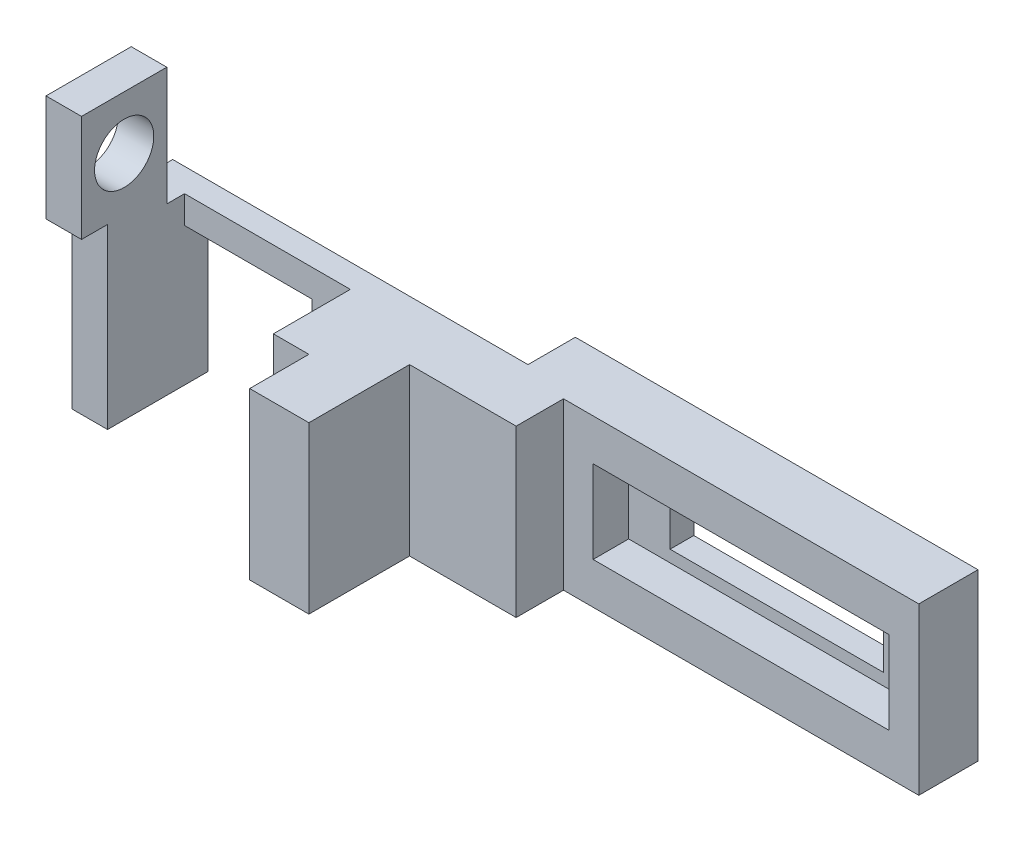
SolidWorks part; units mm, degrees
ref_plane "Front Plane" through (0, 0, 0) normal (0, 0, 1) x (1, 0, 0)
ref_plane "Top Plane" through (0, 0, 0) normal (0, 1, 0) x (1, 0, 0)
ref_plane "Right Plane" through (0, 0, 0) normal (1, 0, 0) x (0, 0, -1)
sketch "Sketch1" plane through (0, 0, 0) normal (0, 1, 0) x (1, 0, 0)
  line L1 (25, 0) -> (25, 8.5)
  line L2 (25, 8.5) -> (34, 8.5)
  line L8 (0, 13.5) -> (30, 13.5)
  line L9 (30, 13.5) -> (30, 17.5)
  line L10 (30, 17.5) -> (64, 17.5)
  line L11 (64, 17.5) -> (64, 12.5)
  line L12 (20, 0) -> (20, 5)
  line L13 (20, 5) -> (0, 5)
  line L14 (20, 0) -> (25, 0)
  line L15 (0, 5) -> (0, 13.5)
  line L17 (0, 0) -> (37.5449, 0) construction
  line L18 (34, 8.5) -> (34, 12.5)
  line L19 (34, 12.5) -> (64, 12.5)
  point P3 (34, 13.5)
  point P15 (0, 0)
  point P17 (62.4601, 13.1956)
  dimension "D1" = 5
  dimension "D2" = 9
  dimension "D3" = 5
  dimension "D4" = 30
  dimension "D5" = 4
  dimension "D6" = 8.5
  dimension "D7" = 5
  dimension "D8" = 20
  dimension "D9" = 5
  dimension "D10" = 4
extrude "Boss-Extrude1" add sketch "Sketch1" along normal blind 14
sketch "Sketch2" plane through (0, 0, -12.5) normal (0, 0, 1) x (1, 0, 0)
  line L0 (64, 7) -> (34, 7) construction
  line L1 (61.5, 3.5) -> (36.5, 3.5)
  line L2 (61.5, 3.5) -> (61.5, 10.5)
  line L3 (61.5, 10.5) -> (36.5, 10.5)
  line L4 (36.5, 3.5) -> (36.5, 10.5)
  line L6 (64, 14) -> (64, 0) construction
  line L7 (49, 3.5) -> (49, 10.5) construction
  line L8 (34, 14) -> (34, 0) construction
  line L11 (61.5, 7) -> (36.5, 7) construction
  line L14 (49, 14) -> (49, 0) construction
  line L15 (34, 14) -> (64, 14) construction
  line L16 (34, 0) -> (64, 0) construction
  dimension "D1" = 25
  dimension "D2" = 7
extrude "Cut-Extrude3" cut sketch "Sketch2" against normal blind 3
sketch "Sketch10" plane through (0, 0, -15.5) normal (0, 0, 1) x (1, 0, 0)
  line L0 (49, 10.5) -> (49, 3.5) construction
  line L1 (58, 9.5) -> (40, 9.5)
  line L2 (58, 9.5) -> (58, 4.5)
  line L3 (58, 4.5) -> (40, 4.5)
  line L4 (40, 9.5) -> (40, 4.5)
  line L5 (58, 9.5) -> (40, 4.5) construction
  line L6 (58, 4.5) -> (40, 9.5) construction
  line L7 (61.5, 10.5) -> (36.5, 10.5) construction
  line L8 (36.5, 3.5) -> (61.5, 3.5) construction
  line L9 (36.5, 7) -> (61.5, 7) construction
  line L10 (36.5, 10.5) -> (36.5, 3.5) construction
  line L11 (61.5, 3.5) -> (61.5, 10.5) construction
  point P0 (49, 7)
  point P11 (49, 9.5)
  point P18 (40, 7)
  dimension "D1" = 18
  dimension "D2" = 5
extrude "Cut-Extrude4" cut sketch "Sketch10" against normal through all
sketch "Sketch11" plane through (0, 0, 0) normal (-1, 0, 0) x (0, 0, 1)
  line L7 (-13.5, 14) -> (-5, 14) construction
  line L12 (-10, 14) -> (-10, 24)
  line L18 (-5, 14) -> (-5, 15)
  line L20 (-10, 14) -> (-5, 14)
  line L23 (-10, 24) -> (-2.8009, 24)
  line L24 (-2.8009, 24) -> (-2.8009, 15)
  line L25 (-2.8009, 15) -> (-5, 15)
  point P0 (-2.8009, 19.7356)
  dimension "D1" = 9
  dimension "D2" = 5
  dimension "D3" = 10
extrude "Boss-Extrude8" add sketch "Sketch11" against normal blind 3
sketch "Sketch12" plane through (3, 0, 0) normal (1, 0, 0) x (0, 0, -1)
  line L0 (2.8009, 15) -> (2.8009, 24) construction
  line L1 (5, 15) -> (2.8009, 15) construction
  circle A0 centre (5.3009, 17.5) radius 2.5
  point P2 (7.543, 27.6234)
  dimension "D1" = 5
extrude "Boss-Extrude9" [suppressed] add sketch "Sketch12" along normal blind 9
ref_plane "Plane1" through (10, 0, 0) normal (-1, 0, 0) x (0, 0, 1)
sketch "Sketch14" plane through (0, 0, -13.5) normal (0, 0, -1) x (-1, 0, 0)
  line L0 (-30, 0) -> (0, 0) construction
  line L1 (-10, 0) -> (-3, 0)
  line L2 (-10, 0) -> (-10, 12)
  line L3 (-10, 12) -> (-3, 12)
  line L4 (-3, 0) -> (-3, 12)
  line L5 (-3, 24) -> (-3, 14) construction
  dimension "D1" = 12
  dimension "D2" = 7
extrude "Cut-Extrude6" [suppressed] cut sketch "Sketch14" against normal blind 9
sketch "Sketch13" plane through (10, 0, 0) normal (-1, 0, 0) x (0, 0, 1)
  line L1 (-13.5, 14) -> (-10, 14) construction
  line L2 (-13.5, 14) -> (-5, 14)
  line L3 (-5, 14) -> (-5, 0)
  line L7 (-5, 0) -> (-7.0993, 0)
  line L8 (-7.0993, 0) -> (-13.5, 14)
  line L9 (-13.5, 0) -> (-5, 0) construction
  line L10 (-5, 14) -> (-5, 0) construction
  line L11 (-5, 15) -> (-5, 0) construction
  line L13 (-13.5, 14) -> (-13.5, 0) construction
  line L14 (-17.5, 14) -> (-13.5, 14) construction
  point P1 (-8.672, 0)
  point P5 (0, 0)
  point P9 (-11.089, 14)
  point P12 (-11.6453, 0)
  point P13 (-7.9977, 14)
  point P14 (-9.7552, 0)
  point P15 (-7.036, 14)
  point P17 (-9.7552, 14)
  point P18 (-11.5747, 14)
  point P19 (-9.5792, 14)
  point P20 (-5, 14)
  point P26 (-5, 0)
  point P28 (-9.4951, 0)
  point P29 (-12.3186, 14)
  point P30 (-10.2652, 14)
  point P31 (-13.5, 14)
  point P33 (-7.0993, 0)
  point P34 (-13.3371, 14)
  point P35 (0, 0)
  point P36 (0, 0)
extrude "Cut-Extrude7" [suppressed] cut sketch "Sketch13" against normal up to surface and the other way up to surface
sketch "Sketch15" plane through (0, 0, 0) normal (-1, 0, 0) x (0, 0, 1)
  line L1 (-6.4004, 24) -> (-6.4004, 15.2416) construction
  line L2 (-2.8009, 24) -> (-10, 24) construction
  line L3 (-2.8009, 19.5) -> (-12.1862, 19.5) construction
  line L4 (-2.8009, 15) -> (-2.8009, 24) construction
  circle A0 centre (-6.4004, 19.5) radius 2.5
  point P10 (0, 0)
  point P11 (0, 0)
  dimension "D1" = 5
extrude "Cut-Extrude8" cut sketch "Sketch15" against normal through all
sketch "Sketch16" plane through (0, 0, -13.5) normal (0, 0, -1) x (-1, 0, 0)
  line L0 (-30, 0) -> (0, 0) construction
  line L1 (-12, 11) -> (-3, 11)
  line L2 (-12, 11) -> (-12, 0)
  line L3 (-12, 0) -> (-3, 0)
  line L4 (-3, 11) -> (-3, 0)
  line L5 (-3, 24) -> (-3, 14) construction
  dimension "D1" = 9
  dimension "D2" = 11
extrude "Cut-Extrude9" [suppressed] cut sketch "Sketch16" against normal blind 9
sketch "Sketch17" [suppressed] plane through (0, 11, 0) normal (0, -1, 0) x (-1, 0, 0)
  line L0 (-12, 5) -> (-12, 13.5) construction
  line L1 (-12, 10.5) -> (-3, 10.5)
  line L2 (-12, 10.5) -> (-12, 5)
  line L3 (-12, 5) -> (-3, 5)
  line L4 (-3, 10.5) -> (-3, 5)
  line L5 (-3, 13.5) -> (-12, 13.5) construction
  dimension "D1" = 3
extrude "Cut-Extrude10" [suppressed] cut sketch "Sketch17" against normal blind 9
sketch "Sketch18" plane through (10, 0, 0) normal (-1, 0, 0) x (0, 0, 1)
  line L0 (-11.5, 14) -> (-11.5, 0)
  line L1 (-11.5, 0) -> (-5, 0)
  line L2 (-5, 0) -> (-5, 14)
  line L3 (-5, 14) -> (-11.5, 14)
  line L4 (-13.5, 14) -> (-13.5, 0) construction
  point P4 (-11.5136, 14)
  point P11 (-13.5, 0)
  point P12 (-11.5, 0)
  dimension "D1" = 2
extrude "Cut-Extrude11" cut sketch "Sketch18" against normal blind 7 and the other way blind 7
sketch "Sketch19" plane through (0, 0, -13.5) normal (0, 0, -1) x (-1, 0, 0)
  line L0 (-30, 0) -> (0, 0) construction
  line L1 (-13.7627, 0) -> (-3, 0)
  line L2 (-13.7627, 0) -> (-13.7627, 11.672)
  line L3 (-13.7627, 11.672) -> (-3, 11.672)
  line L4 (-3, 0) -> (-3, 11.672)
  line L5 (-3, 24) -> (-3, 14) construction
extrude "Cut-Extrude12" cut sketch "Sketch19" against normal blind 7
